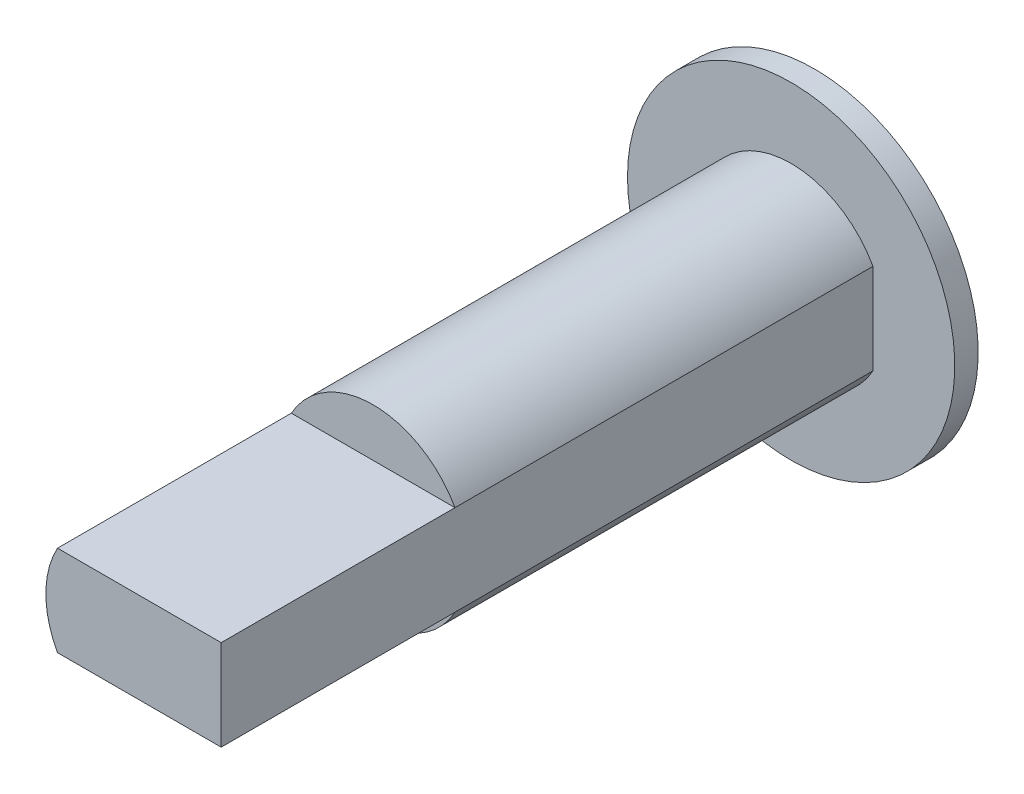
SolidWorks part; units mm, degrees
ref_plane "Front Plane" through (0, 0, 0) normal (0, 0, 1) x (1, 0, 0)
ref_plane "Top Plane" through (0, 0, 0) normal (0, 1, 0) x (1, 0, 0)
ref_plane "Right Plane" through (0, 0, 0) normal (1, 0, 0) x (0, 0, -1)
sketch "Sketch1" plane through (0, 0, 0) normal (0, 0, 1) x (1, 0, 0)
  line L0 (3.5, 1.9365) -> (3.5, -1.9365)
  arc A0 (3.5, 1.9365) -> (3.5, -1.9365) centre (0, 0) ccw
  arc A1 (3.5, -1.9365) -> (3.5, 1.9365) centre (0, 0) ccw construction
  dimension "D1" = 3.5
  dimension "8" = 8
extrude "Boss-Extrude1" add sketch "Sketch1" against normal blind 27.8796
sketch "Sketch2" plane through (0, 0, 0) normal (0, 0, 1) x (1, 0, 0)
  line L0 (3.5, -1.9365) -> (3.5, 1.9365) construction
  line L1 (3.5, -1.9365) -> (3.5, 1.9365) construction
  line L2 (3.5, 1.9365) -> (-3.5, 1.9365)
  line L3 (3.5, -1.9365) -> (-3.5, -1.9365)
  arc A0 (3.5, 1.9365) -> (3.5, -1.9365) centre (0, 0) ccw construction
  arc A1 (3.5, 1.9365) -> (-3.5, 1.9365) centre (0, 0) ccw
  arc A2 (-3.5, 1.9365) -> (-3.5, -1.9365) centre (0, 0) ccw construction
  arc A3 (-3.5, -1.9365) -> (3.5, -1.9365) centre (0, 0) ccw
extrude "Cut-Extrude1" cut sketch "Sketch2" against normal blind 10
sketch "Sketch3" plane through (0, 0, -27.8796) normal (0, 0, -1) x (-1, 0, 0)
  circle A0 centre (0, 0) radius 7
  dimension "D1" = 14
extrude "Boss-Extrude2" add sketch "Sketch3" along normal blind 1
